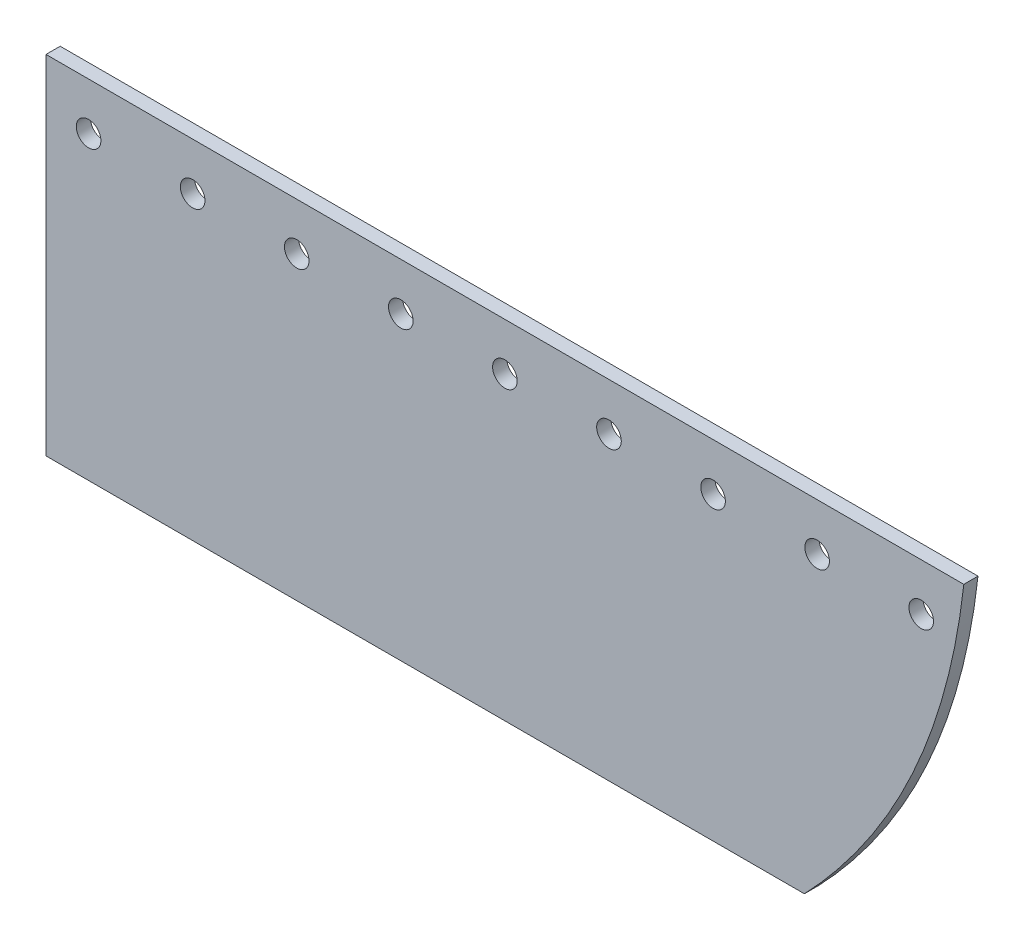
SolidWorks part; units mm, degrees
ref_plane "前视基准面" through (0, 0, 0) normal (0, 0, 1) x (1, 0, 0)
ref_plane "上视基准面" through (0, 0, 0) normal (0, 1, 0) x (1, 0, 0)
ref_plane "右视基准面" through (0, 0, 0) normal (1, 0, 0) x (0, 0, -1)
sketch "草图1" plane through (0, 0, 0) normal (0, 0, 1) x (1, 0, 0)
  line L0 (-100, 26.75) -> (100, 26.75) construction
  line L1 (-100, 36.75) -> (100, 36.75)
  line L2 (-100, 36.75) -> (-100, -36.75)
  line L3 (-100, -36.75) -> (100, -36.75)
  line L4 (100, 36.75) -> (100, -36.75)
  line L5 (-100, 36.75) -> (100, -36.75) construction
  line L6 (-100, -36.75) -> (100, 36.75) construction
  point P0 (0, 0)
  dimension "D1" = 73.5
  dimension "D2" = 200
  dimension "D3" = 10
extrude "凸台-拉伸1" add sketch "草图1" along normal blind 3
sketch "草图2" plane through (0, 0, 3) normal (0, 0, 1) x (1, 0, 0)
  line L0 (-100, 26.75) -> (100, 26.75) construction
  line L1 (-100, 36.75) -> (-100, -36.75) construction
  line L2 (100, -36.75) -> (100, 36.75) construction
  line L4 (100, 36.75) -> (-100, 36.75) construction
  circle A0 centre (0, 26.75) radius 2.6
  dimension "D1" = 5.2
  dimension "D2" = 10
extrude "切除-拉伸2" cut sketch "草图2" against normal through all both and the other way through all
pattern_linear "阵列(线性)1" count 5 spacing 22 along (1, 0, 0) count 5 spacing 22 along (-1, 0, 0) of "切除-拉伸2"
sketch "草图3" plane through (0, 0, 3) normal (0, 0, 1) x (1, 0, 0)
  line L0 (-100, -36.75) -> (100, -36.75) construction
  line L1 (-100, 36.75) -> (-97, 36.75)
  line L2 (-100, 36.75) -> (-100, -36.75)
  line L3 (-100, -36.75) -> (-97, -36.75)
  line L4 (-97, 36.75) -> (-97, -36.75)
  line L6 (100, 36.75) -> (97, 36.75)
  line L7 (100, 36.75) -> (100, -36.75)
  line L8 (100, -36.75) -> (97, -36.75)
  line L9 (97, 36.75) -> (97, -36.75)
  dimension "D1" = 3
  dimension "D2" = 3
extrude "切除-拉伸3" cut sketch "草图3" against normal through all both and the other way through all
sketch "草图4" plane through (0, 0, 3) normal (0, 0, 1) x (1, 0, 0)
  line L0 (-97, -36.75) -> (97, -36.75) construction
  line L1 (63.3032, -36.75) -> (97, -36.75)
  line L2 (97, -36.75) -> (97, 36.75)
  spline S0 degree 2 poles (63.3032, -36.75) (92.1891, -6.5259) (97, 36.75) knots 0 0 0 1 1 1
extrude "切除-拉伸4" cut sketch "草图4" against normal through all both and the other way through all
